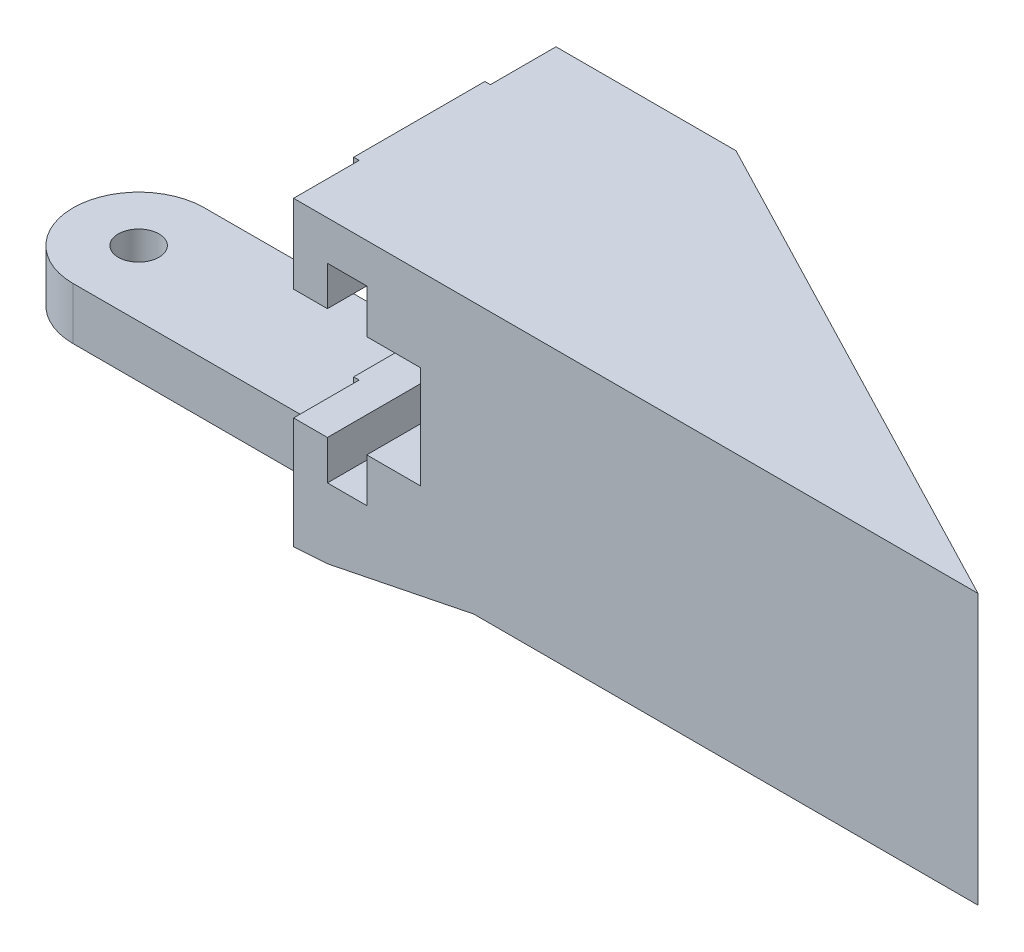
SolidWorks part; units mm, degrees
ref_plane "前视基准面" through (0, 0, 0) normal (0, 0, 1) x (1, 0, 0)
ref_plane "上视基准面" through (0, 0, 0) normal (0, 1, 0) x (1, 0, 0)
ref_plane "右视基准面" through (0, 0, 0) normal (1, 0, 0) x (0, 0, -1)
sketch "草图1" plane through (0, 0, 0) normal (0, 0, 1) x (1, 0, 0)
  line L0 (-13.1003, 11.5) -> (39.49, 11.5)
  line L1 (39.49, 11.5) -> (39.49, -9.0832)
  line L2 (39.49, -9.0832) -> (1.0443, -9.0832)
  line L3 (1.0443, -9.0832) -> (-7.4163, -10.7953)
  line L4 (-10.024, -11.323) -> (-12.6787, -11.5)
  line L5 (-12.6787, -11.5) -> (-39.49, -11.5)
  line L6 (-39.49, -11.5) -> (-39.49, -7.5361)
  line L7 (-39.49, -7.5361) -> (-13.1003, -7.5)
  line L8 (-13.1003, -7.5) -> (-13.1003, -3)
  line L9 (-13.1003, -3) -> (-10.1003, -3)
  line L10 (-10.1003, -3) -> (-10.1003, -6)
  line L11 (-10.1003, -6) -> (-7.1003, -6)
  line L12 (-7.1003, -6) -> (-7.1003, -2.65)
  line L13 (-7.1003, -2.65) -> (-3.0003, -2.65)
  line L14 (-3.0003, -2.65) -> (-3.0003, 5.15)
  line L15 (-3.0003, 5.15) -> (-7.1003, 5.15)
  line L16 (-7.1003, 5.15) -> (-7.1003, 8.5)
  line L17 (-7.1003, 8.5) -> (-10.1003, 8.5)
  line L18 (-10.1003, 8.5) -> (-10.1003, 5.5)
  line L19 (-10.1003, 5.5) -> (-13.1003, 5.5)
  line L20 (-13.1003, 5.5) -> (-13.1003, 11.5)
  line L21 (-10.024, -11.323) -> (-7.4163, -10.7953)
extrude "凸台-拉伸1" add sketch "草图1" along normal blind 20
sketch "草图2" plane through (0, -9.0832, 0) normal (0, -1, 0) x (1, 0, 0)
  line L0 (39.49, 20) -> (39.49, 0)
  line L1 (39.49, 0) -> (1.0443, 0)
  line L2 (1.0443, 0) -> (39.49, 20)
extrude "切除-拉伸1" cut sketch "草图2" against normal through all both and the other way through all
sketch "草图3" plane through (0, -11.5, 0) normal (0, -1, 0) x (1, 0, 0)
  line L0 (-12.6787, 20) -> (-12.6787, 15)
  line L1 (-12.6787, 20) -> (-12.6787, 0) construction
  line L2 (-12.6787, 15) -> (-39.49, 15)
  line L3 (-39.49, 20) -> (-39.49, 0) construction
  line L4 (-39.49, 15) -> (-39.49, 20)
  line L5 (-39.49, 20) -> (-12.6787, 20)
  line L6 (-12.6787, 0) -> (-12.6787, 5)
  line L7 (-12.6787, 5) -> (-39.49, 5)
  line L8 (-39.49, 5) -> (-39.49, 0)
  line L9 (-39.49, 0) -> (-12.6787, 0) construction
  line L10 (-39.49, 0) -> (-12.6787, 0)
extrude "切除-拉伸2" cut sketch "草图3" against normal through all both and the other way through all
sketch "草图4" plane through (0, -11.5, 0) normal (0, -1, 0) x (1, 0, 0)
  line L0 (-39.49, 15) -> (-34.49, 15)
  line L1 (-12.6787, 15) -> (-39.49, 15) construction
  line L2 (-39.49, 15) -> (-39.49, 5)
  line L3 (-39.49, 5) -> (-12.6787, 5) construction
  line L4 (-39.49, 15) -> (-39.49, 5) construction
  line L5 (-39.49, 5) -> (-34.49, 5)
  arc A0 (-34.49, 15) -> (-34.49, 5) centre (-34.49, 10) ccw
  circle A1 centre (-34.49, 10) radius 1.55
  line M2 (-12.6787, 15) -> (-39.49, 15)
  line M3 (-39.49, 15) -> (-39.49, 5)
  line M4 (-39.49, 5) -> (-12.6787, 5)
extrude "切除-拉伸3" cut sketch "草图4" against normal through all both and the other way through all contours A0 M2 M3 | A1 | A0 L2 M4
